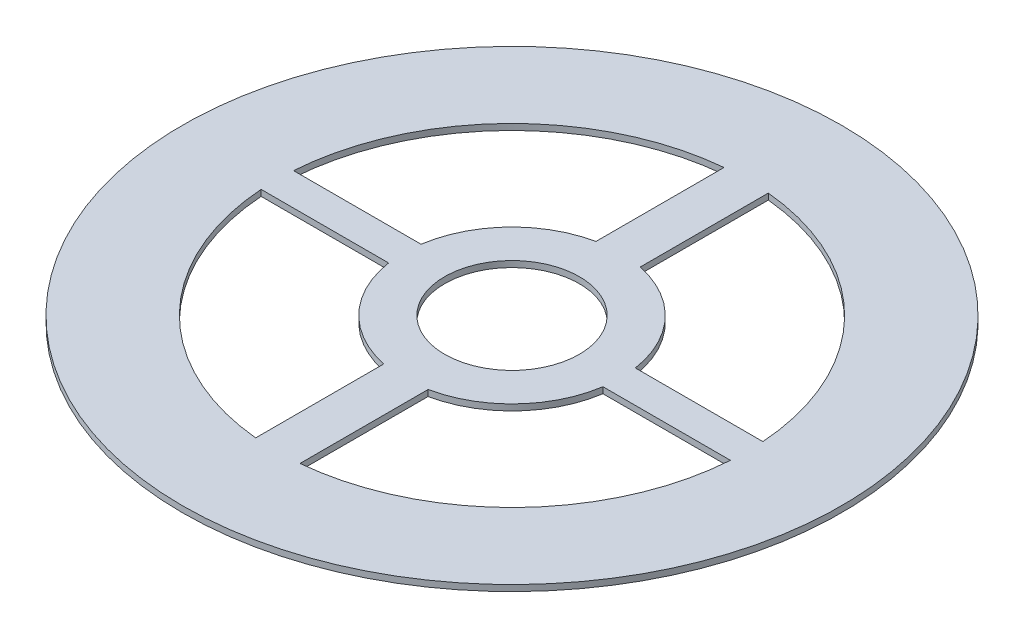
SolidWorks part; units mm, degrees
ref_plane "Front Plane" through (0, 0, 0) normal (0, 0, 1) x (1, 0, 0)
ref_plane "Top Plane" through (0, 0, 0) normal (0, 1, 0) x (1, 0, 0)
ref_plane "Right Plane" through (0, 0, 0) normal (1, 0, 0) x (0, 0, -1)
sketch "Sketch1" plane through (0, 0, 0) normal (0, 1, 0) x (1, 0, 0)
  line L1 (52.5483, -7.956) -> (115.0829, -7.956)
  line L3 (52.5483, 7.956) -> (115.0829, 7.956)
  line L7 (-115.0829, -7.956) -> (-52.5483, -7.956)
  line L9 (-115.0829, 7.956) -> (-52.5483, 7.956)
  line L14 (-10.8606, 52.0256) -> (-10.8606, 114.8452)
  line L16 (10.8606, 52.0256) -> (10.8606, 114.8452)
  line L20 (-10.8606, -114.8452) -> (-10.8606, -52.0256)
  line L22 (10.8606, -114.8452) -> (10.8606, -52.0256)
  arc A0 (-115.0829, -7.956) -> (-10.8606, -114.8452) centre (0, 0) ccw
  circle A1 centre (0, 0) radius 33.0196
  arc A2 (-52.5483, -7.956) -> (-10.8606, -52.0256) centre (0, 0) ccw
  circle A3 centre (0, 0) radius 161.6263
  arc A4 (-10.8606, 52.0256) -> (-52.5483, 7.956) centre (0, 0) ccw
  arc A5 (-10.8606, 114.8452) -> (-115.0829, 7.956) centre (0, 0) ccw
  arc A6 (52.5483, 7.956) -> (10.8606, 52.0256) centre (0, 0) ccw
  arc A7 (115.0829, 7.956) -> (10.8606, 114.8452) centre (0, 0) ccw
  arc A8 (10.8606, -114.8452) -> (115.0829, -7.956) centre (0, 0) ccw
  arc A9 (10.8606, -52.0256) -> (52.5483, -7.956) centre (0, 0) ccw
  point P6 (66.1738, 0)
  point P11 (-67.9418, 0)
  point P16 (0, 66.3)
  point P21 (0, -68.5732)
extrude "Boss-Extrude1" add sketch "Sketch1" along normal blind 3
